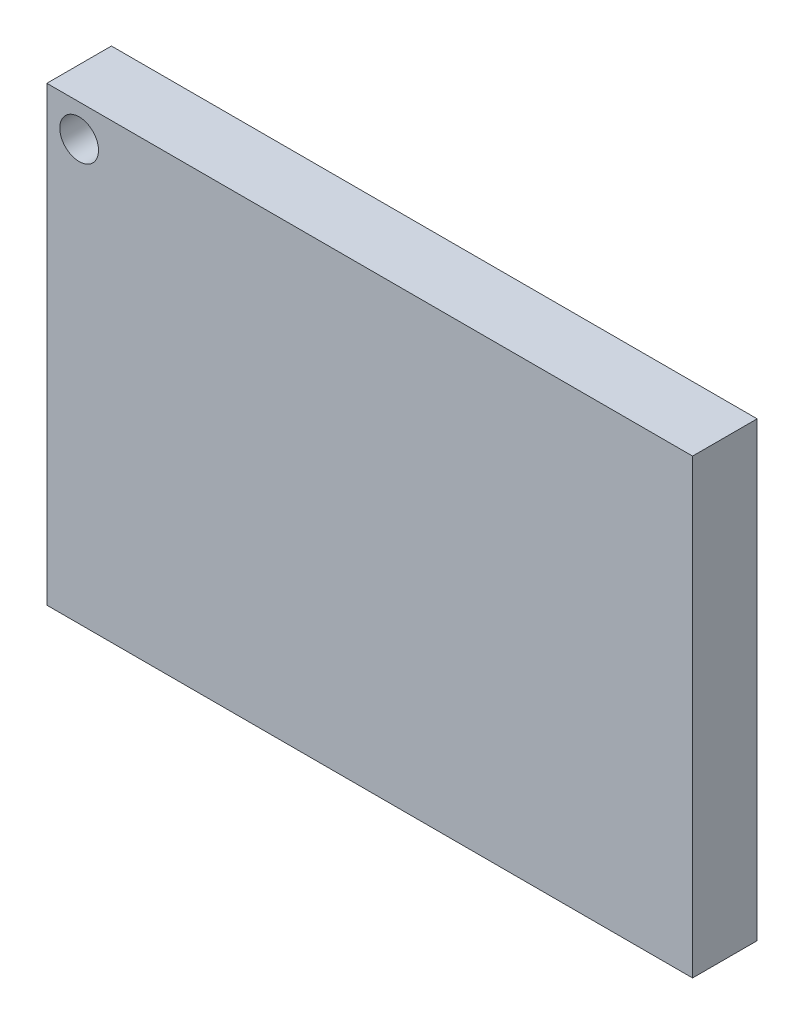
SolidWorks part; units mm, degrees
ref_plane "前视基准面" through (0, 0, 0) normal (0, 0, 1) x (1, 0, 0)
ref_plane "上视基准面" through (0, 0, 0) normal (0, 1, 0) x (1, 0, 0)
ref_plane "右视基准面" through (0, 0, 0) normal (1, 0, 0) x (0, 0, -1)
sketch "草图1" plane through (0, 0, 0) normal (0, 0, 1) x (1, 0, 0)
  line L1 (-50, 35) -> (50, 35)
  line L2 (-50, 35) -> (-50, -35)
  line L3 (-50, -35) -> (50, -35)
  line L4 (50, 35) -> (50, -35)
  line L5 (-50, 35) -> (50, -35) construction
  line L6 (-50, -35) -> (50, 35) construction
  point P0 (0, 0)
  dimension "D1" = 70
  dimension "D2" = 100
extrude "凸台-拉伸1" add sketch "草图1" along normal mid plane 10
sketch "草图2" plane through (0, 0, 5) normal (0, 0, 1) x (1, 0, 0)
  line L0 (50, 35) -> (-50, 35) construction
  line L2 (-50, 35) -> (-50, -35) construction
  circle A0 centre (-45, 30) radius 3
  point P6 (-58.9262, 34.0763)
  point P7 (0, 0)
  point P9 (-50, 22.4129)
  dimension "D1" = 5
  dimension "D2" = 5
extrude "切除-拉伸1" cut sketch "草图2" against normal blind 10
pattern_linear "阵列(线性)1" count 5 spacing 10 along (0, 0, 1) count 5 spacing 10 along (0, 0, 1) of "切除-拉伸1"
